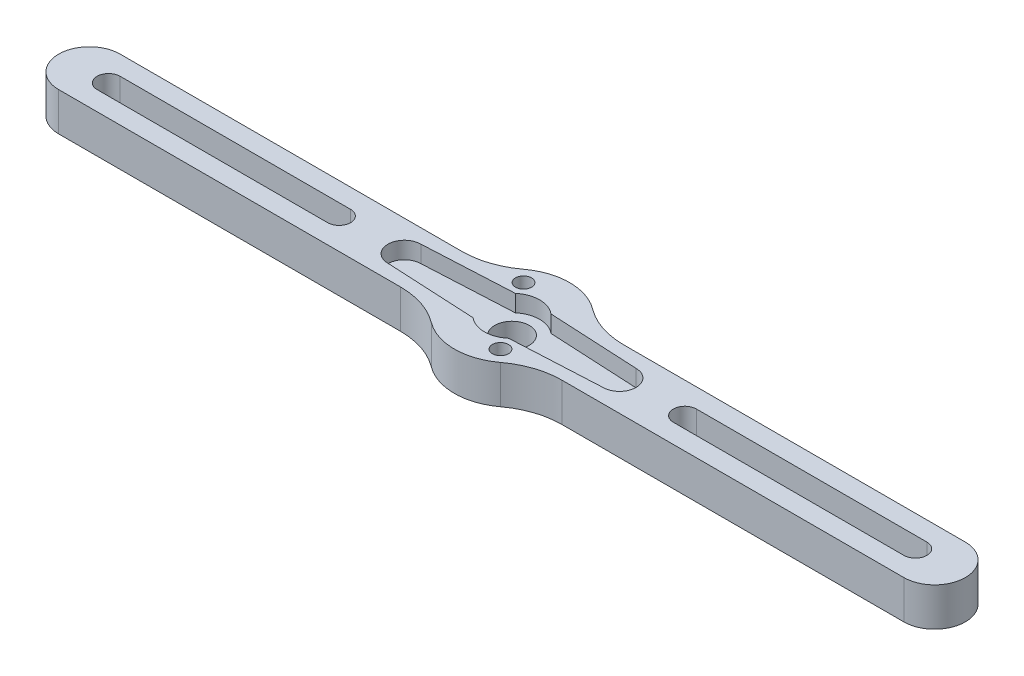
SolidWorks part; units mm, degrees
ref_plane "Plan de face" through (0, 0, 0) normal (0, 0, 1) x (1, 0, 0)
ref_plane "Plan de dessus" through (0, 0, 0) normal (0, 1, 0) x (1, 0, 0)
ref_plane "Plan de droite" through (0, 0, 0) normal (1, 0, 0) x (0, 0, -1)
sketch "Esquisse1" plane through (0, 0, 0) normal (0, 1, 0) x (1, 0, 0)
  line L0 (0, 28.0707) -> (0, -34.7894) construction
  line L1 (-60.5826, 0) -> (56.3691, 0) construction
  line L2 (-6.3443, 4) -> (-55, 4)
  line L3 (-55, -4) -> (-6.3443, -4)
  line L6 (-55, 4) -> (-55, -4) construction
  line L7 (-2.5495, 7.4631) -> (-2.5495, -10.8207) construction
  line L8 (2.5495, 7.4631) -> (2.5495, -10.8207) construction
  line L9 (55, 4) -> (55, -4) construction
  line L12 (55, -4) -> (6.3443, -4)
  line L13 (6.3443, 4) -> (55, 4)
  line L14 (-22.5, 0) -> (-52.5, 0) construction
  line L15 (-22.5, -1.5) -> (-52.5, -1.5)
  line L16 (-22.5, 1.5) -> (-52.5, 1.5)
  line L17 (22.5, 0) -> (52.5, 0) construction
  line L18 (22.5, -1.5) -> (52.5, -1.5)
  line L19 (22.5, 1.5) -> (52.5, 1.5)
  circle A0 centre (0, 0) radius 7.5 construction
  arc A1 (-55, 4) -> (-55, -4) centre (-55, 0) ccw
  circle A2 centre (0, 0) radius 3.75 construction
  arc A7 (-6.3443, 4) -> (6.3443, 4) centre (0, 0) cw
  arc A8 (-6.3443, -4) -> (6.3443, -4) centre (0, 0) ccw
  arc A11 (55, 4) -> (55, -4) centre (55, 0) cw
  circle A12 centre (-3, 4.5) radius 1.05
  circle A13 centre (3, -4.5) radius 1.05
  circle A14 centre (0, 0) radius 2.25
  arc A15 (-22.5, -1.5) -> (-22.5, 1.5) centre (-22.5, 0) ccw
  arc A16 (-52.5, 1.5) -> (-52.5, -1.5) centre (-52.5, 0) ccw
  arc A17 (22.5, -1.5) -> (22.5, 1.5) centre (22.5, 0) cw
  arc A18 (52.5, 1.5) -> (52.5, -1.5) centre (52.5, 0) cw
  point P17 (-37.5, 0)
  point P33 (37.5, 0)
  dimension "D1" = 8
  dimension "D2" = 15
  dimension "D3" = 7.5
  dimension "D4" = 55
  dimension "D5" = 4.5
  dimension "D8" = 3
  dimension "D10" = 4.5
  dimension "D12" = 2.1
  dimension "D6" = 30
  dimension "D7" = 3
  dimension "D9" = 4.5
  dimension "D11" = 3
  dimension "D13" = 37.5
extrude "Boss.-Extru.1" add sketch "Esquisse1" along normal blind 5
sketch "Esquisse2" plane through (0, 5, 0) normal (0, 1, 0) x (1, 0, 0)
  line L0 (0, 0) -> (-19.3823, 0) construction
  line L1 (0, 8.3279) -> (0, -9.0401) construction
  line L2 (-2.3233, 6.255) -> (-2.3233, -9.5886) construction
  line L3 (-14, 2.15) -> (-2.3233, 2.75)
  line L4 (55, 4) -> (6.3443, 4)
  line L5 (-6.3443, 4) -> (-55, 4)
  line L6 (-55, -4) -> (-6.3443, -4)
  line L7 (6.3443, -4) -> (55, -4)
  line L8 (55, 4) -> (6.3443, 4)
  line L9 (-6.3443, 4) -> (-55, 4)
  line L10 (-55, -4) -> (-6.3443, -4)
  line L11 (6.3443, -4) -> (55, -4)
  line L12 (-14, -2.15) -> (-2.3233, -2.75)
  line L13 (14, -2.15) -> (2.3233, -2.75)
  line L14 (14, 2.15) -> (2.3233, 2.75)
  circle A0 centre (0, 0) radius 3.6 construction
  circle A1 centre (-14, 0) radius 2.15 construction
  arc A2 (-14, 2.15) -> (-14, -2.15) centre (-14, 0) ccw
  arc A3 (2.3233, 2.75) -> (-2.3233, 2.75) centre (0, 0) ccw
  arc A4 (55, -4) -> (55, 4) centre (55, 0) ccw
  arc A5 (6.3443, 4) -> (-6.3443, 4) centre (0, 0) ccw
  arc A6 (-55, 4) -> (-55, -4) centre (-55, 0) ccw
  arc A7 (-6.3443, -4) -> (6.3443, -4) centre (0, 0) ccw
  arc A8 (55, -4) -> (55, 4) centre (55, 0) ccw
  arc A9 (6.3443, 4) -> (-6.3443, 4) centre (0, 0) ccw
  arc A10 (-55, 4) -> (-55, -4) centre (-55, 0) ccw
  arc A11 (-6.3443, -4) -> (6.3443, -4) centre (0, 0) ccw
  arc A12 (-2.3233, -2.75) -> (2.3233, -2.75) centre (0, 0) ccw
  arc A13 (14, 2.15) -> (14, -2.15) centre (14, 0) cw
  dimension "D2" = 7.2
  dimension "D3" = 4.3
  dimension "D4" = 14
  dimension "D5" = 5.5
  dimension "D1" = 0
extrude "Enlèv. mat.-Extru.1" cut sketch "Esquisse2" against normal blind 2.2 contours A3 L3 A2 L12 A12 L13 A13 L14
fillet "Congé1" radius 10 4 edges at (6.3443, 2.5, 4) (-6.3443, 2.5, 4) (6.3443, 2.5, -4) (-6.3443, 2.5, -4)
